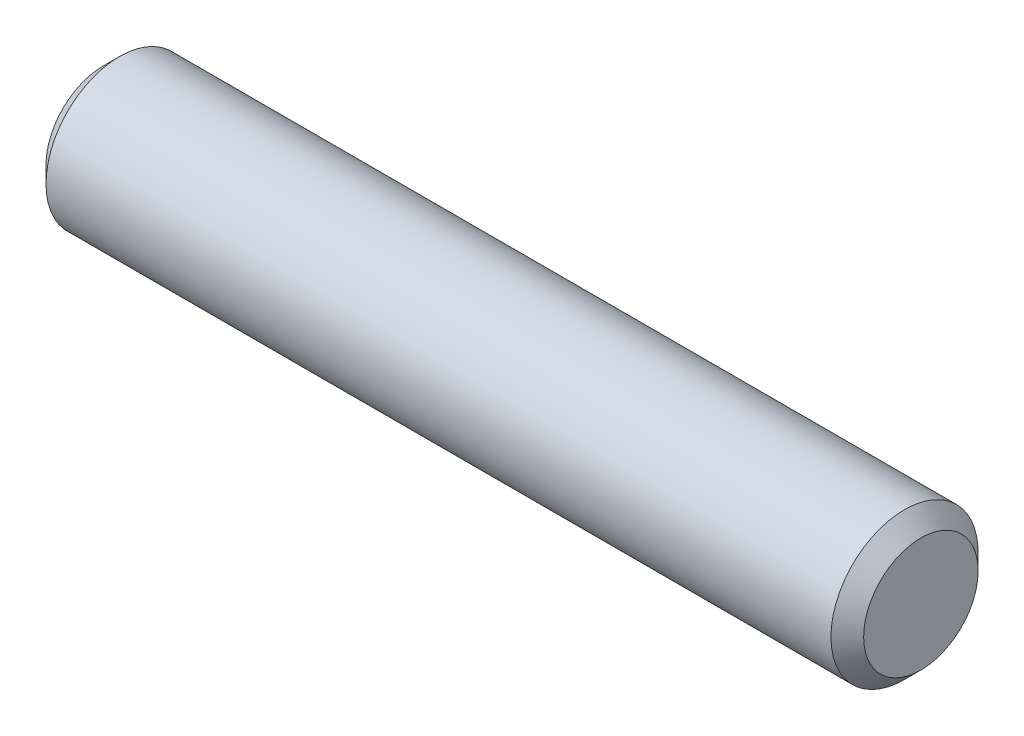
SolidWorks part; units mm, degrees
ref_plane "前视基准面" through (0, 0, 0) normal (0, 0, 1) x (1, 0, 0)
ref_plane "上视基准面" through (0, 0, 0) normal (0, 1, 0) x (1, 0, 0)
ref_plane "右视基准面" through (0, 0, 0) normal (1, 0, 0) x (0, 0, -1)
sketch "草图1" plane through (0, 0, 0) normal (0, 0, 1) x (1, 0, 0)
  line L0 (-6.3202, 0) -> (6.9944, 0) construction
  line L1 (-5.3427, 0) -> (-5.3427, 0.9)
  line L2 (-5.3427, 0.9) -> (4.6573, 0.9)
  line L3 (4.6573, 0.9) -> (4.6573, 0)
  line L4 (-5.3427, 0) -> (4.6573, 0)
  dimension "D1" = 10
  dimension "D2" = 0.9
revolve "旋转1" add sketch "草图1" angle 360 about L0
chamfer "倒角1" distance 0.2 angle 45 2 edges at (-5.3427, 0, 0.9) (4.6573, 0, 0.9)
